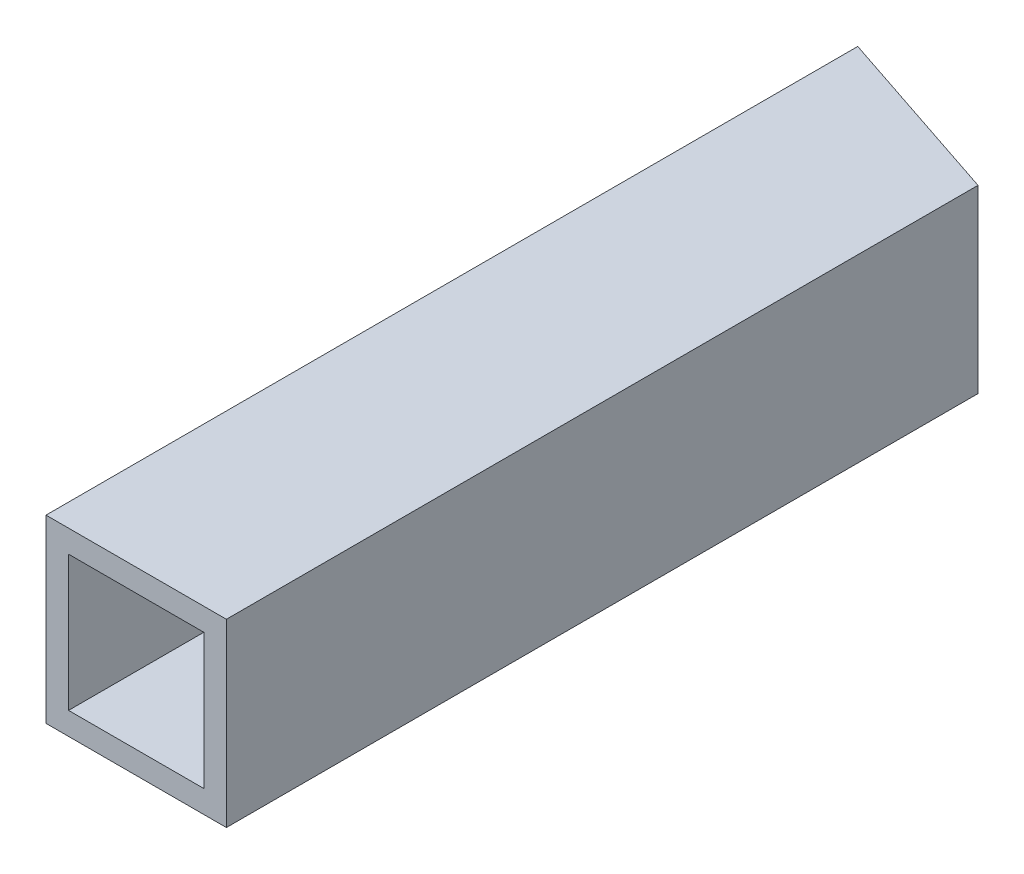
SolidWorks part; units mm, degrees
ref_plane "Front Plane" through (0, 0, 0) normal (0, 0, 1) x (1, 0, 0)
ref_plane "Top Plane" through (0, 0, 0) normal (0, 1, 0) x (1, 0, 0)
ref_plane "Right Plane" through (0, 0, 0) normal (1, 0, 0) x (0, 0, -1)
sketch "Sketch1" plane through (0, 0, 0) normal (0, 0, 1) x (1, 0, 0)
  line L1 (0, 0) -> (25.4, 0)
  line L2 (0, 0) -> (0, 25.4)
  line L3 (0, 25.4) -> (25.4, 25.4)
  line L4 (25.4, 0) -> (25.4, 25.4)
  line L5 (3.175, 22.225) -> (22.225, 22.225)
  line L6 (3.175, 22.225) -> (3.175, 3.175)
  line L7 (3.175, 3.175) -> (22.225, 3.175)
  line L8 (22.225, 22.225) -> (22.225, 3.175)
  dimension "D1" = 25.4
  dimension "D2" = 25.4
  dimension "D3" = 3.175
  dimension "D4" = 3.175
  dimension "D5" = 3.175
  dimension "D6" = 3.175
extrude "Boss-Extrude1" add sketch "Sketch1" along normal blind 114.3
sketch "Sketch2" plane through (0, 25.4, 0) normal (0, 1, 0) x (1, 0, 0)
  line L0 (0, 0) -> (25.4, -8.4692)
  line L1 (25.4, -114.3) -> (25.4, 0) construction
  line L2 (25.4, 0) -> (0, 0) construction
  line L3 (0, 0) -> (25.4, 0)
  line L4 (25.4, 0) -> (25.4, -8.4692)
  dimension "D1" = 18.44
extrude "Cut-Extrude1" cut sketch "Sketch2" against normal through all contours L0 L4 L3
